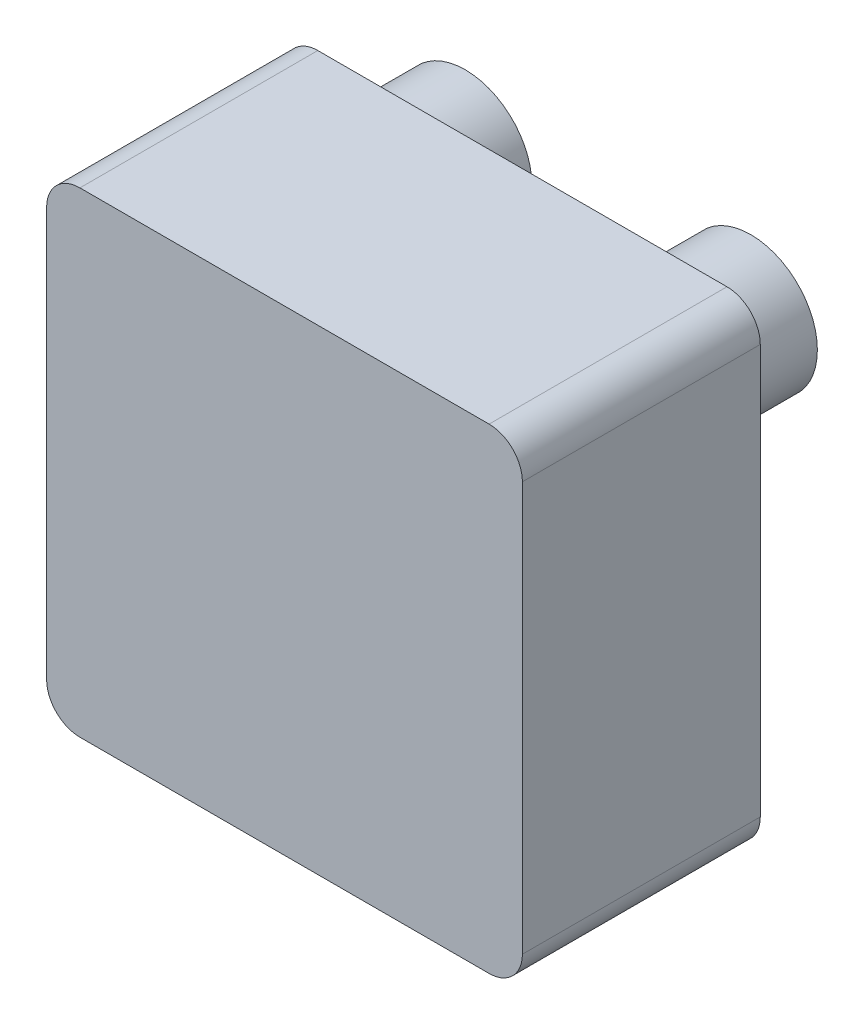
SolidWorks part; units mm, degrees
ref_plane "Front Plane" through (0, 0, 0) normal (0, 0, 1) x (1, 0, 0)
ref_plane "Top Plane" through (0, 0, 0) normal (0, 1, 0) x (1, 0, 0)
ref_plane "Right Plane" through (0, 0, 0) normal (1, 0, 0) x (0, 0, -1)
sketch "Sketch2" plane through (0, 0, 0) normal (0, 1, 0) x (1, 0, 0)
  line L1 (0, 0) -> (10, 0)
  line L2 (0, 0) -> (0, 5)
  line L3 (0, 5) -> (10, 5)
  line L4 (10, 0) -> (10, 5)
  dimension "D1" = 10
  dimension "D2" = 5
extrude "Boss-Extrude2" add sketch "Sketch2" along normal blind 10
sketch "Sketch3" plane through (0, 0, -5) normal (0, 0, -1) x (-1, 0, 0)
  line L0 (-10, 10) -> (0, 10) construction
  line L1 (-10, 10) -> (-10, 0) construction
  line L2 (0, 10) -> (0, 0) construction
  circle A0 centre (-8, 8) radius 1.4
  circle A1 centre (-2, 8) radius 1.4
  dimension "D1" = 2.8
  dimension "D2" = 2.8
  dimension "D4" = 2
  dimension "D3" = 2
  dimension "D5" = 2
  dimension "D6" = 2
extrude "Boss-Extrude3" add sketch "Sketch3" along normal blind 1.8
sketch "Sketch4" plane through (0, 0, 0) normal (0, -1, 0) x (1, 0, 0)
  line L0 (0.6, -5) -> (3.4, -5) construction
  line L1 (2.5, -5) -> (4.35, -5)
  line L2 (2.5, -5) -> (2.5, -4.65)
  line L3 (2.5, -4.65) -> (4.35, -4.65)
  line L4 (4.35, -5) -> (4.35, -4.65)
  line L5 (10, -5) -> (0, -5) construction
  line L6 (5.65, -5) -> (7.5, -5)
  line L7 (5.65, -5) -> (5.65, -4.65)
  line L8 (5.65, -4.65) -> (7.5, -4.65)
  line L9 (7.5, -5) -> (7.5, -4.65)
  line L10 (0, -5) -> (0, 0) construction
  line L11 (10, 0) -> (10, -5) construction
  dimension "D1" = 2.5
  dimension "D2" = 2.5
  dimension "D3" = 0.35
  dimension "D4" = 0.35
  dimension "D5" = 1.3
  dimension "D6" = 1.85
extrude "Cut-Extrude1" cut sketch "Sketch4" against normal blind 5
sketch "Sketch5" plane through (0, 0, 0) normal (0, -1, 0) x (1, 0, 0)
  line L0 (0, -2.5) -> (10, -2.5) construction
  line L1 (0, -5) -> (0, 0) construction
  line L2 (10, 0) -> (10, -5) construction
  line L3 (5, 0) -> (5, -5) construction
  line L4 (0, 0) -> (10, 0) construction
  line L5 (5.65, -5) -> (4.35, -5) construction
  circle A0 centre (5, -2.5) radius 1.2
  dimension "D1" = 2.4
extrude "Cut-Extrude2" cut sketch "Sketch5" against normal blind 3.5
fillet "Fillet1" radius 0.7 4 edges at (10, 0, -2.5) (0, 0, -2.5) (0, 10, -2.5) (10, 10, -2.5)
